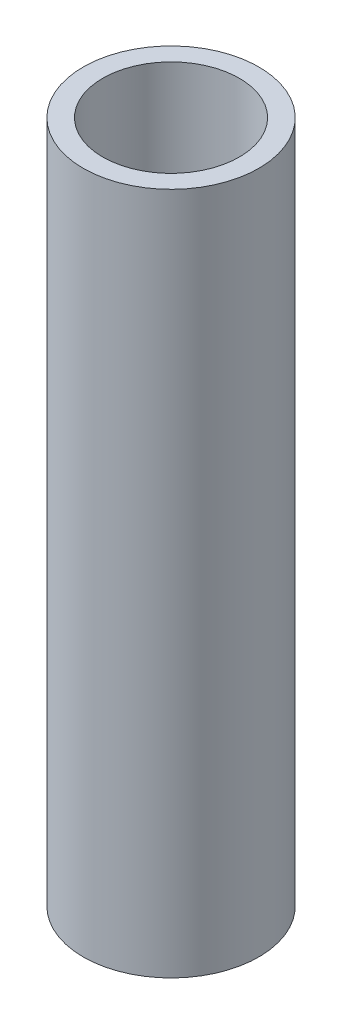
SolidWorks part; units mm, degrees
ref_plane "Front Plane" through (0, 0, 0) normal (0, 0, 1) x (1, 0, 0)
ref_plane "Top Plane" through (0, 0, 0) normal (0, 1, 0) x (1, 0, 0)
ref_plane "Right Plane" through (0, 0, 0) normal (1, 0, 0) x (0, 0, -1)
sketch "Sketch1" plane through (0, 0, 0) normal (0, 1, 0) x (1, 0, 0)
  circle A0 centre (0, 0) radius 9
  circle A1 centre (0, 0) radius 7
  dimension "D1" = 18
  dimension "D2" = 14
extrude "Boss-Extrude1" add sketch "Sketch1" along normal blind 70
